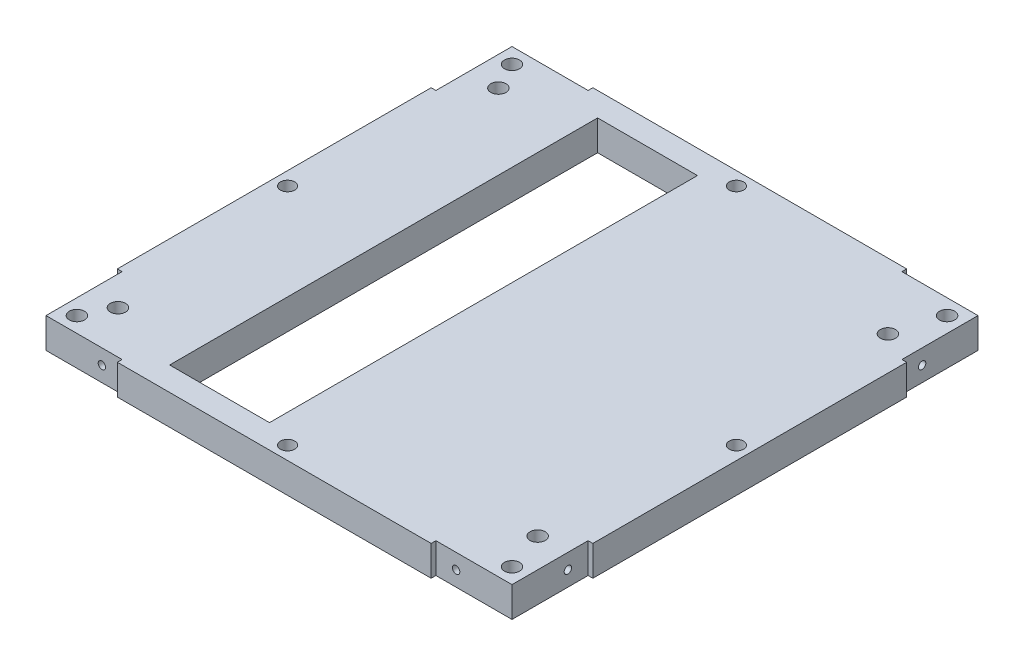
SolidWorks part; units mm, degrees
material "6061-O (SS)"
ref_plane "Front Plane" through (0, 0, 0) normal (0, 0, 1) x (1, 0, 0)
ref_plane "Top Plane" through (0, 0, 0) normal (0, 1, 0) x (1, 0, 0)
ref_plane "Right Plane" through (0, 0, 0) normal (1, 0, 0) x (0, 0, -1)
sketch "Sketch1" plane through (0, 0, 0) normal (0, 1, 0) x (1, 0, 0)
  line L0 (0, 83) -> (1, 83)
  line L1 (0, 0) -> (100, 0)
  line L2 (0, 0) -> (0, 100)
  line L3 (0, 100) -> (100, 100)
  line L4 (100, 0) -> (100, 100)
  line L5 (1, 83) -> (1, 99)
  line L6 (1, 99) -> (17, 99)
  line L7 (17, 99) -> (17, 100)
  line L8 (17, 100) -> (0, 100)
  line L9 (0, 83) -> (0, 100)
  line L10 (83, 100) -> (83, 99)
  line L11 (83, 99) -> (99, 99)
  line L12 (99, 99) -> (99, 83)
  line L13 (99, 83) -> (100, 83)
  line L14 (100, 83) -> (100, 100)
  line L15 (83, 100) -> (100, 100)
  line L16 (100, 0) -> (83, 0)
  line L17 (83, 0) -> (83, 1)
  line L18 (83, 1) -> (99, 1)
  line L19 (99, 1) -> (99, 17)
  line L20 (99, 17) -> (100, 17)
  line L21 (100, 17) -> (100, 0)
  line L22 (0, 0) -> (0, 17)
  line L23 (0, 17) -> (1, 17)
  line L24 (1, 17) -> (1, 1)
  line L25 (1, 1) -> (17, 1)
  line L26 (17, 1) -> (17, 0)
  line L27 (17, 0) -> (0, 0)
  dimension "D1" = 100
  dimension "D2" = 100
  dimension "D3" = 1
  dimension "D4" = 1
  dimension "D5" = 17
  dimension "D6" = 17
  dimension "D7" = 1
  dimension "D8" = 1
  dimension "D9" = 17
  dimension "D10" = 17
  dimension "D11" = 17
  dimension "D12" = 17
  dimension "D13" = 1
  dimension "D14" = 1
  dimension "D15" = 1
  dimension "D16" = 1
  dimension "D17" = 17
  dimension "D18" = 17
extrude "Boss-Extrude1" add sketch "Sketch1" along normal blind 6.35 contours L25 L26 L1 L17 L18 L19 L20 L4 L13 L12 L11 L10 L3 L7 L6 L5 L0 L2 L23 L24
extrude "Cut-Extrude3" cut sketch "Sketch4" against normal mid plane 5080 contours A3
sketch "Sketch4" plane through (-170.7665, -217.0542, -269.3086) normal (0, -1, 0) x (0, 0, -1)
  circle A0 centre (-179.3036, 177.9015) radius 1.2
  circle A1 centre (-259.3136, 177.9015) radius 1.2
  circle A2 centre (-256.7736, 263.6315) radius 1.2
  circle A3 centre (-183.1136, 263.6315) radius 1.2
  dimension "D1" = 2.4
  dimension "D2" = 2.4
  dimension "D3" = 2.4
  dimension "D4" = 2.4
sketch "Sketch7" plane through (0, 0, 0) normal (0, -1, 0) x (1, 0, 0)
  line L1 (1, -1) -> (8, -1)
  line L2 (1, -1) -> (1, -6)
  line L3 (1, -6) -> (8, -6)
  line L4 (8, -1) -> (8, -6)
  line L5 (99, -1) -> (92, -1)
  line L6 (99, -1) -> (99, -6)
  line L7 (99, -6) -> (92, -6)
  line L8 (92, -1) -> (92, -6)
  line L9 (1, -99) -> (8, -99)
  line L10 (1, -99) -> (1, -94)
  line L11 (1, -94) -> (8, -94)
  line L12 (8, -99) -> (8, -94)
  line L13 (99, -99) -> (92, -99)
  line L14 (99, -99) -> (99, -94)
  line L15 (99, -94) -> (92, -94)
  line L16 (92, -99) -> (92, -94)
  dimension "D1" = 7
  dimension "D2" = 5
  dimension "D3" = 7
  dimension "D4" = 5
  dimension "D5" = 7
  dimension "D6" = 5
  dimension "D7" = 7
  dimension "D8" = 5
sketch "Sketch30" plane through (0, 0, 0) normal (0, -1, 0) x (1, 0, 0)
  line L0 (0, -17) -> (0, -83) construction
  line L1 (17, 0) -> (83, 0) construction
  line L2 (17, -100) -> (83, -100) construction
  circle A0 centre (50, -33.5) radius 1.5
  circle A1 centre (50, -66.5) radius 1.5
  circle A2 centre (35, -26.5) radius 1.5
  circle A3 centre (35, -35.5) radius 1.5
  dimension "D1" = 3
  dimension "D2" = 3
  dimension "D3" = 3
  dimension "D4" = 3
  dimension "D5" = 35
  dimension "D6" = 35
  dimension "D7" = 50
  dimension "D8" = 50
  dimension "D9" = 28
  dimension "D10" = 9
  dimension "D11" = 33.5
  dimension "D12" = 33.5
extrude "Cut-Extrude4" [suppressed] cut sketch "Sketch30" against normal blind 10
sketch "Sketch129" plane through (99, 0, 0) normal (1, 0, 0) x (0, 0, -1)
  line L0 (99, 0) -> (83, 0) construction
  line L1 (1, 0) -> (17, 0) construction
  line L2 (17, 6.35) -> (17, 0) construction
  line L3 (83, 6.35) -> (83, 0) construction
  circle A0 centre (12.75, 3.175) radius 0.775
  circle A1 centre (87.25, 3.175) radius 0.775
  dimension "D5" = 1.55
  dimension "D6" = 1.55
  dimension "D1" = 3.175
  dimension "D2" = 3.175
  dimension "D3" = 4.25
  dimension "D4" = 4.25
extrude "Cut-Extrude5" cut sketch "Sketch129" against normal blind 3
sketch "Sketch130" plane through (0, 0, -1) normal (0, 0, 1) x (1, 0, 0)
  line L0 (1, 6.35) -> (17, 6.35) construction
  line L1 (83, 6.35) -> (99, 6.35) construction
  line L2 (83, 6.35) -> (83, 0) construction
  line L3 (17, 6.35) -> (17, 0) construction
  circle A0 centre (87.25, 3.175) radius 0.775
  circle A1 centre (12.75, 3.175) radius 0.775
  dimension "D5" = 1.55
  dimension "D6" = 1.55
  dimension "D1" = 3.175
  dimension "D2" = 3.175
  dimension "D3" = 4.25
  dimension "D4" = 4.25
extrude "Cut-Extrude6" cut sketch "Sketch130" against normal blind 8
sketch "Sketch131" plane through (1, 0, 0) normal (-1, 0, 0) x (0, 0, 1)
  line L0 (-83, 6.35) -> (-99, 6.35) construction
  line L1 (-17, 6.35) -> (-1, 6.35) construction
  line L2 (-17, 6.35) -> (-17, 0) construction
  line L3 (-83, 6.35) -> (-83, 0) construction
  circle A0 centre (-12.75, 3.175) radius 0.775
  circle A1 centre (-87.25, 3.175) radius 0.775
  dimension "D5" = 1.55
  dimension "D6" = 1.55
  dimension "D1" = 3.175
  dimension "D2" = 3.175
  dimension "D3" = 4.25
  dimension "D4" = 4.25
extrude "Cut-Extrude7" cut sketch "Sketch131" against normal blind 8
sketch "Sketch132" plane through (0, 0, -99) normal (0, 0, -1) x (-1, 0, 0)
  line L0 (-83, 6.35) -> (-99, 6.35) construction
  line L1 (-1, 6.35) -> (-17, 6.35) construction
  line L2 (-17, 6.35) -> (-17, 0) construction
  line L3 (-83, 6.35) -> (-83, 0) construction
  circle A0 centre (-87.25, 3.175) radius 0.775
  circle A1 centre (-12.75, 3.175) radius 0.775
  dimension "D5" = 1.55
  dimension "D6" = 1.55
  dimension "D1" = 3.175
  dimension "D2" = 3.175
  dimension "D3" = 4.25
  dimension "D4" = 4.25
extrude "Cut-Extrude8" cut sketch "Sketch132" against normal blind 8
sketch "Sketch133" plane through (0, 6.35, 0) normal (0, 1, 0) x (1, 0, 0)
  line L0 (17, 100) -> (83, 100) construction
  line L1 (0, 17) -> (0, 83) construction
  line L2 (17, 0) -> (83, 0) construction
  line L3 (100, 17) -> (100, 83) construction
  circle A0 centre (4.25, 95.75) radius 1.6
  circle A1 centre (4.25, 4.25) radius 1.6
  circle A2 centre (95.75, 95.75) radius 1.6
  circle A3 centre (95.75, 4.25) radius 1.6
  dimension "D1" = 3.2
  dimension "D4" = 3.2
  dimension "D5" = 3.2
  dimension "D6" = 3.2
  dimension "D2" = 4.25
  dimension "D3" = 4.25
  dimension "D7" = 4.25
  dimension "D8" = 4.25
  dimension "D9" = 4.25
  dimension "D10" = 4.25
  dimension "D11" = 4.25
  dimension "D12" = 4.25
extrude "Cut-Extrude9" cut sketch "Sketch133" against normal blind 10
sketch "Sketch134" plane through (0, 6.35, 0) normal (0, 1, 0) x (1, 0, 0)
  circle A0 centre (92.865, 86.195) radius 1.6
  circle A1 centre (92.865, 12.535) radius 1.6
  circle A2 centre (7.135, 9.995) radius 1.6
  circle A3 centre (7.135, 90.005) radius 1.6
  dimension "D1" = 3.2
  dimension "D2" = 3.2
  dimension "D3" = 3.2
  dimension "D4" = 3.2
extrude "Cut-Extrude10" cut sketch "Sketch134" against normal blind 10
sketch "Sketch135" plane through (0, 0, 0) normal (0, -1, 0) x (1, 0, 0)
  line L0 (50, -50) -> (2.8068, -50) construction
  line L3 (50, -50) -> (50, -2.8068) construction
  line L5 (50, -50) -> (50, -97.1932) construction
  line L8 (50, -50) -> (97.1932, -50) construction
  circle A0 centre (2.8068, -50) radius 1.5
  circle A1 centre (50, -2.8068) radius 1.5
  circle A2 centre (97.1932, -50) radius 1.5
  circle A3 centre (50, -97.1932) radius 1.5
  text T0 "Bottom"
  dimension "D2" = 3
  dimension "D1" = 47.1932
extrude "Cut-Extrude11" cut sketch "Sketch135" against normal through all contours A0 | A3 | A2 | A1
sketch "Sketch136" plane through (0, 0, 0) normal (0, -1, 0) x (1, 0, 0)
  line L0 (17, 0) -> (83, 0) construction
  line L1 (23, -5) -> (44, -5)
  line L2 (23, -5) -> (23, -95)
  line L3 (23, -95) -> (44, -95)
  line L4 (44, -5) -> (44, -95)
  line L5 (17, -1) -> (17, 0) construction
  dimension "D1" = 90
  dimension "D2" = 21
  dimension "D3" = 5
  dimension "D4" = 6
extrude "Cut-Extrude12" cut sketch "Sketch136" against normal through all
